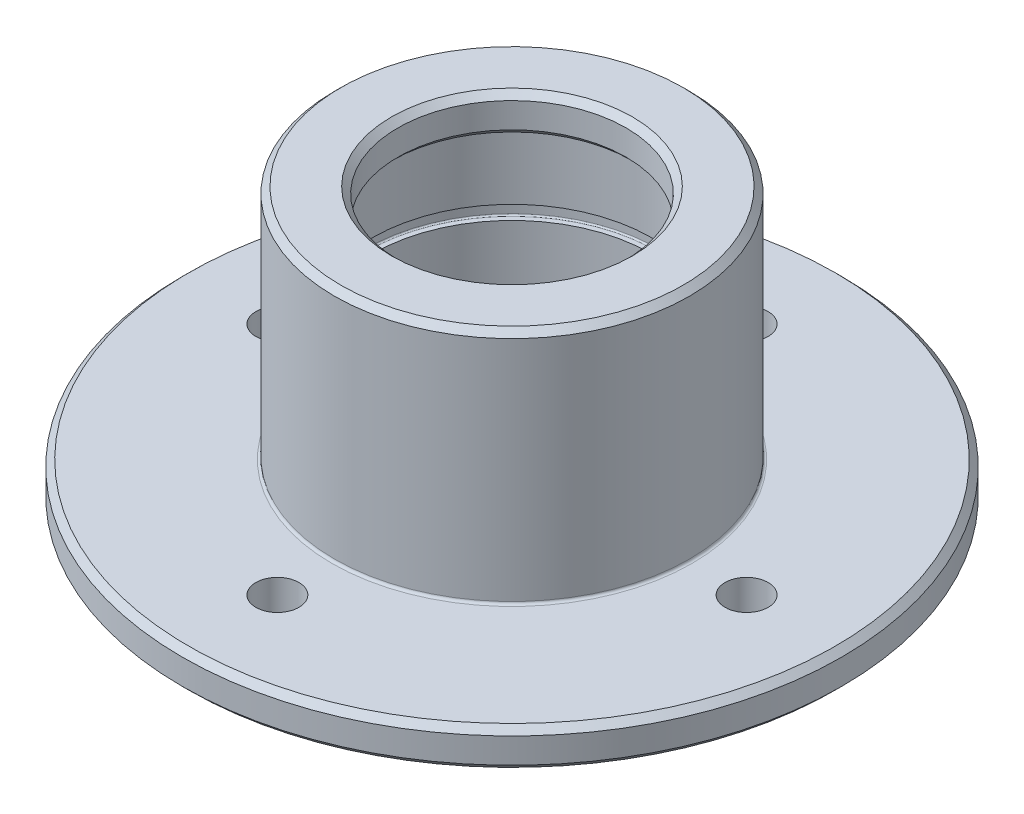
SolidWorks part; units mm, degrees
ref_plane "Front" through (0, 0, 0) normal (0, 0, 1) x (1, 0, 0)
ref_plane "Top" through (0, 0, 0) normal (0, 1, 0) x (1, 0, 0)
ref_plane "Right" through (0, 0, 0) normal (1, 0, 0) x (0, 0, -1)
sketch "Sketch1" plane through (0, 0, 0) normal (0, 0, 1) x (1, 0, 0)
  line L0 (0, 17.954) -> (0, -17.7415) construction
  line L2 (11, -3) -> (11, 15.65)
  line L4 (14, 18.65) -> (14, 0)
  line L5 (14, 0) -> (26, 0)
  line L6 (26, 0) -> (26, -3)
  line L7 (26, -3) -> (11, -3)
  line L9 (14, 18.65) -> (9, 18.65)
  line L10 (9, 18.65) -> (9, 15.65)
  line L11 (9, 15.65) -> (11, 15.65)
  line L13 (5, 9.65) -> (-5, 9.65) construction
  dimension "D1" = 3
  dimension "D2" = 11
  dimension "D3" = 9
  dimension "D4" = 12
  dimension "D5" = 3
  dimension "D6" = 3
  dimension "D7" = 6
revolve "Revolve1" add sketch "Sketch1" angle 360 about L0
sketch "Sketch2" [suppressed] plane through (0, 0, 0) normal (0, 1, 0) x (1, 0, 0)
  circle A0 centre (0, 0) radius 11
extrude "Cut-Extrude1" [suppressed] cut sketch "Sketch2" against normal through all
ref_plane "Plane1" through (0, 17.954, 0) normal (-1, 0, 0) x (0, 0, 1)
sketch "Sketch4" plane through (0, 17.954, 0) normal (-1, 0, 0) x (0, 0, 1)
  line L0 (11.39, -9.404) -> (9.9, -9.404)
  line L1 (9.9, -9.404) -> (9.9, -8.304)
  line L2 (9.9, -8.304) -> (11.39, -8.304)
  line L3 (11.5, -8.414) -> (11.5, -9.294)
  line L4 (0, -50) -> (0, 50) construction
  line L7 (-11, -2.304) -> (11, -2.304) construction
  arc A0 (11.5, -9.294) -> (11.39, -9.404) centre (11.39, -9.294) cw
  arc A1 (11.5, -8.414) -> (11.39, -8.304) centre (11.39, -8.414) ccw
  dimension "D1" = 0.11
  dimension "D2" = 0.11
  dimension "D3" = 6
  dimension "D4" = 1.1
  dimension "D5" = 9.9
  dimension "D6" = 1.6
revolve "Groove for BS 3673 P4 - B022M, Internal Circlip1" cut sketch "Sketch4"
hole_wizard "M3 Clearance Hole1" positions "Sketch5" profile "Sketch6" hole size "M3" standard "ISO" end condition through all
sketch "Sketch5" plane through (0, 0, 0) normal (0, 1, 0) x (1, 0, 0)
  circle A0 centre (0, 0) radius 18.5 construction
  circle A1 centre (0, 0) radius 26 construction
  point P0 (0, 18.5)
  point P7 (18.5, 0)
  point P9 (0, -18.5)
  point P11 (-18.5, 0)
  dimension "D1" = 7.5
  dimension "D2" = 37
sketch "Sketch6" plane through (0, 0, -18.5) normal (1, 0, 0) x (0, 0, 1)
  line L0 (0, 0) -> (0, 3)
  line L1 (0, 3) -> (1.7, 3)
  line L2 (1.7, 3) -> (1.7, 0)
  line L5 (1.7, 0) -> (0, 0)
  line L11 (0, -6.35) -> (0, 107.95) construction
  dimension "Thru Hole Dia." = 3.4
  dimension "Thru Hole Depth" = 3
fillet "Fillet1" radius 0.2 1 edges at (0, 15.65, 11)
fillet "Fillet2" radius 0.2 1 edges at (0, 0, 14)
chamfer "Chamfer1" distance 0.5 angle 45 6 edges at (0, -3, 11) (0, 18.65, 14) (0, 18.65, 9) (0, 15.65, 9) (0, -3, 26) (0, 0, 26)
